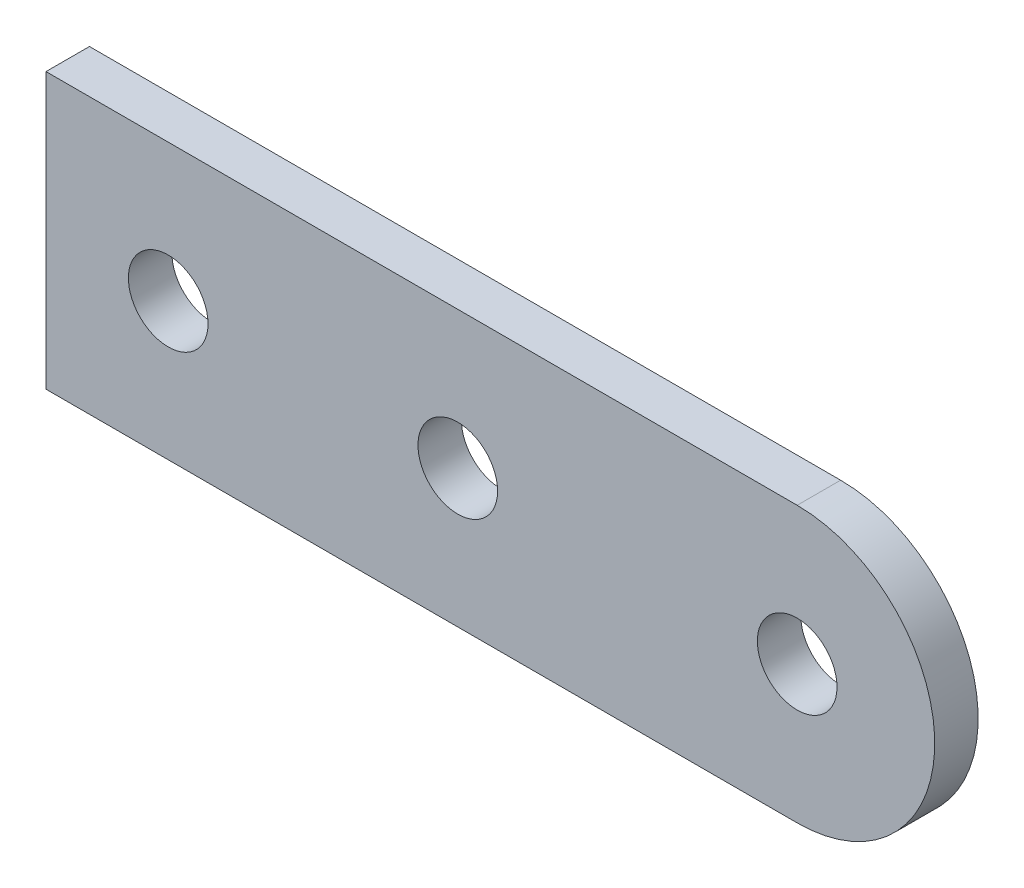
SolidWorks part; units mm, degrees
ref_plane "Front Plane" through (0, 0, 0) normal (0, 0, 1) x (1, 0, 0)
ref_plane "Top Plane" through (0, 0, 0) normal (0, 1, 0) x (1, 0, 0)
ref_plane "Right Plane" through (0, 0, 0) normal (1, 0, 0) x (0, 0, -1)
sketch "Sketch1" plane through (0, 0, 0) normal (0, 0, 1) x (1, 0, 0)
  line L0 (-51.88, 0) -> (18.2346, 0) construction
  line L1 (-51.88, -9.5) -> (0, -9.5)
  line L2 (-51.88, 9.5) -> (-51.88, -9.5)
  line L3 (-51.88, 9.5) -> (0, 9.5)
  line L4 (-51.88, -3.5) -> (-51.88, 3.5) construction
  line L11 (-15, 9.5) -> (-515, 9.5) construction
  arc A0 (0, -9.5) -> (0, 9.5) centre (0, 0) ccw
extrude "Boss-Extrude1" add sketch "Sketch1" along normal blind 3
hole_wizard "M5 Clearance Hole1" positions "Sketch5" profile "Sketch4" hole size "M5" standard "ISO" end condition up to next
sketch "Sketch5" plane through (0, 0, 3) normal (0, 0, 1) x (1, 0, 0)
  circle A0 centre (-43.44, 0) radius 2.1 construction
  point P0 (-43.44, 0)
sketch "Sketch4" plane through (-43.44, 0, 3) normal (1, 0, 0) x (0, -1, 0)
  line L0 (0, 0) -> (0, 3)
  line L1 (0, 3) -> (2.75, 3)
  line L2 (2.75, 3) -> (2.75, 0)
  line L5 (2.75, 0) -> (0, 0)
  line L11 (0, -6.35) -> (0, 107.95) construction
  dimension "Thru Hole Dia." = 5.5
  dimension "Thru Hole Depth" = 3
hole_wizard "M5 Clearance Hole2" positions "Sketch7" profile "Sketch6" hole size "M5" standard "ISO" end condition up to next
sketch "Sketch7" plane through (0, 0, 3) normal (0, 0, 1) x (1, 0, 0)
  circle A0 centre (-23.44, 0) radius 2.1 construction
  point P0 (-23.44, 0)
sketch "Sketch6" plane through (-23.44, 0, 3) normal (1, 0, 0) x (0, -1, 0)
  line L0 (0, 0) -> (0, 3)
  line L1 (0, 3) -> (2.75, 3)
  line L2 (2.75, 3) -> (2.75, 0)
  line L5 (2.75, 0) -> (0, 0)
  line L11 (0, -6.35) -> (0, 107.95) construction
  dimension "Thru Hole Dia." = 5.5
  dimension "Thru Hole Depth" = 3
hole_wizard "M5 Clearance Hole3" positions "Sketch9" profile "Sketch8" hole size "M5" standard "ISO" end condition up to next
sketch "Sketch9" plane through (0, 0, 3) normal (0, 0, 1) x (1, 0, 0)
  point P0 (0, 0)
sketch "Sketch8" plane through (0, 0, 3) normal (1, 0, 0) x (0, -1, 0)
  line L0 (0, 0) -> (0, 3)
  line L1 (0, 3) -> (2.75, 3)
  line L2 (2.75, 3) -> (2.75, 0)
  line L5 (2.75, 0) -> (0, 0)
  line L11 (0, -6.35) -> (0, 107.95) construction
  dimension "Thru Hole Dia." = 5.5
  dimension "Thru Hole Depth" = 3
